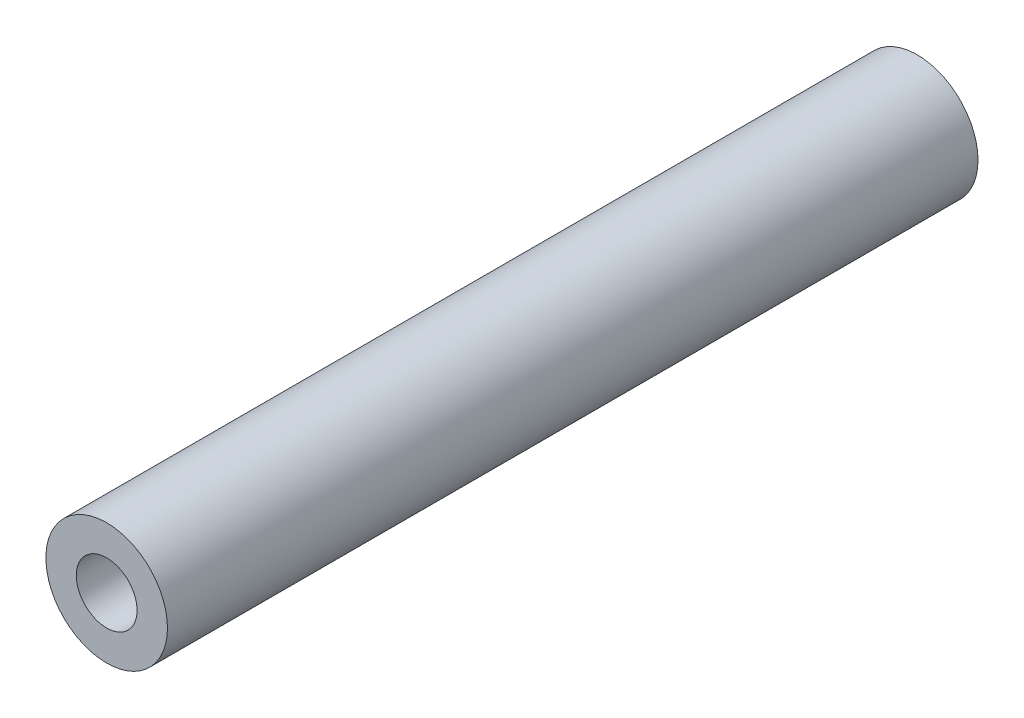
SolidWorks part; units mm, degrees
ref_plane "前视基准面" through (0, 0, 0) normal (0, 0, 1) x (1, 0, 0)
ref_plane "上视基准面" through (0, 0, 0) normal (0, 1, 0) x (1, 0, 0)
ref_plane "右视基准面" through (0, 0, 0) normal (1, 0, 0) x (0, 0, -1)
sketch "草图1" plane through (0, 0, 0) normal (0, 0, 1) x (1, 0, 0)
  circle A0 centre (0, 0) radius 3
  circle A1 centre (0, 0) radius 1.5
  dimension "D1" = 6
  dimension "D2" = 3
extrude "凸台-拉伸1" add sketch "草图1" along normal blind 40
